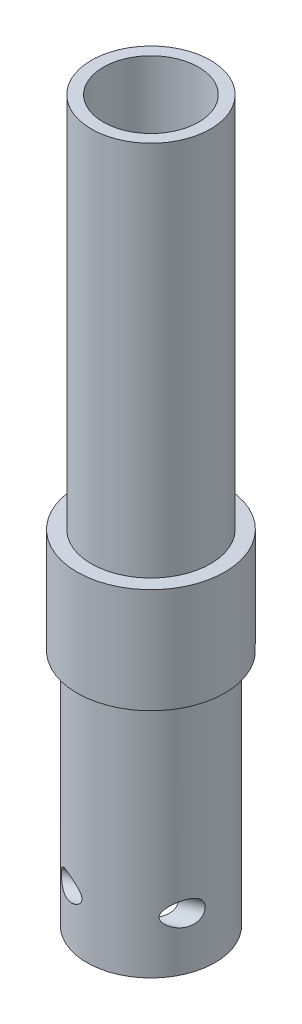
SolidWorks part; units mm, degrees
material "Polylactide (PLA)"
ref_plane "Front Plane" through (0, 0, 0) normal (0, 0, 1) x (1, 0, 0)
ref_plane "Top Plane" through (0, 0, 0) normal (0, 1, 0) x (1, 0, 0)
ref_plane "Right Plane" through (0, 0, 0) normal (1, 0, 0) x (0, 0, -1)
sketch "Sketch1" plane through (0, 0, 0) normal (0, 1, 0) x (1, 0, 0)
  circle A0 centre (0, 0) radius 13.45
  circle A1 centre (0, 0) radius 10
  dimension "D1" = 20
  dimension "D2" = 26.9
extrude "Boss-Extrude1" add sketch "Sketch1" along normal blind 100
sketch "Sketch6" plane through (0, 100, 0) normal (0, 1, 0) x (1, 0, 0)
  circle A0 centre (0, 0) radius 12.5
  circle A1 centre (0, 0) radius 10
  dimension "D1" = 20
  dimension "D2" = 25
extrude "Boss-Extrude2" add sketch "Sketch6" along normal blind 85 and the other way blind 4
sketch "Sketch7" plane through (0, 0, 0) normal (0, -1, 0) x (1, 0, 0)
  circle A0 centre (0, 0) radius 10
  circle A1 centre (0, 0) radius 15.5
  dimension "D1" = 20
  dimension "D2" = 31
extrude "Boss-Extrude3" add sketch "Sketch7" along normal blind 1 from offset 85 offset against normal yes
sketch "Sketch11" plane through (0, 0, 0) normal (1, 0, 0) x (0, 0, -1)
  line L1 (-17.505, -1.2) -> (17.505, -1.2)
  line L2 (-17.505, -1.2) -> (-17.505, 1.2)
  line L3 (-17.505, 1.2) -> (17.505, 1.2)
  line L4 (17.505, -1.2) -> (17.505, 1.2)
  line L5 (-17.505, -1.2) -> (17.505, 1.2) construction
  line L6 (-17.505, 1.2) -> (17.505, -1.2) construction
  point P0 (0, 0)
  dimension "D1" = 2.4
extrude "Cut-Extrude1" cut sketch "Sketch11" against normal through all both and the other way through all
sketch "Sketch13" plane through (0, 0, 0) normal (0, 0, 1) x (1, 0, 0)
  line L1 (-13.45, 1.2) -> (19.1091, 1.2)
  line L2 (-13.45, 1.2) -> (-13.45, 44)
  line L3 (-13.45, 44) -> (19.1091, 44)
  line L4 (19.1091, 1.2) -> (19.1091, 44)
  dimension "D1" = 42.8
extrude "Cut-Extrude3" cut sketch "Sketch13" against normal through all both and the other way through all
sketch "Sketch14" plane through (0, 85, 0) normal (0, 1, 0) x (1, 0, 0)
  circle A1 centre (0, 0) radius 15.5
  circle A2 centre (0, 0) radius 15.5
  dimension "D1" = 0
extrude "Boss-Extrude4" add sketch "Sketch14" along normal blind 21
sketch "Sketch15" plane through (0, 85, 0) normal (0, -1, 0) x (1, 0, 0)
  circle A0 centre (0, 0) radius 10
extrude "Cut-Extrude4" cut sketch "Sketch15" against normal blind 22
sketch "Sketch17" plane through (0, 44, 0) normal (0, -1, 0) x (1, 0, 0)
  circle A0 centre (0, 0) radius 10
  circle A1 centre (0, 0) radius 13.45
  circle A2 centre (0, 0) radius 13.45
  circle A3 centre (0, 0) radius 13.45
  circle M3 centre (0, 0) radius 10
  circle M4 centre (0, 0) radius 13.45
  dimension "D1" = 0
extrude "Boss-Extrude5" add sketch "Sketch17" along normal blind 10 contours M4 M3
sketch "Sketch18" plane through (35.019, 0, -14.7536) normal (0.9216, 0, -0.3883) x (-0.3883, 0, -0.9216)
  line L0 (-13.45, 84) -> (-13.45, 34) construction
  line L1 (-13.45, 34) -> (13.45, 34) construction
  circle A0 centre (-9.45, 45) radius 2.5
  dimension "D1" = 4
  dimension "D2" = 11
extrude "Cut-Extrude5" cut sketch "Sketch18" against normal blind 54
sketch "Sketch20" plane through (0, 0, 0) normal (0, 0, 1) x (1, 0, 0)
  line L0 (15.5, 84) -> (-15.5, 84)
  line L1 (0, 84) -> (0, 71.5)
  circle A0 centre (0, 71.5) radius 2
  dimension "D1" = 12.5
  dimension "D2" = 4
extrude "Cut-Extrude6" cut sketch "Sketch20" against normal blind 22 contours A0
